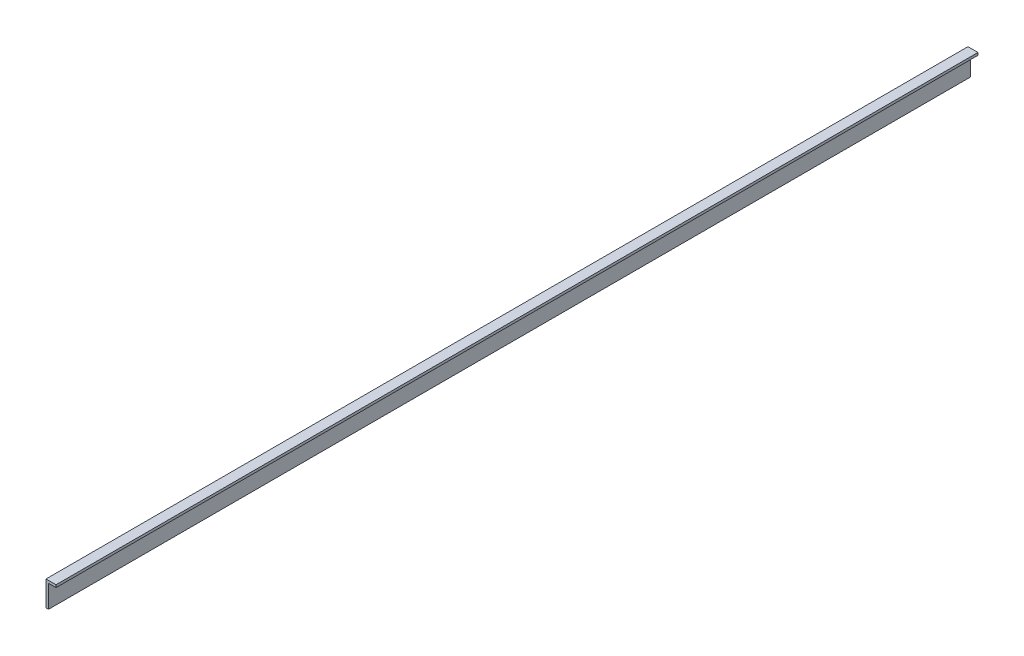
SolidWorks part; units mm, degrees
ref_plane "Front Plane" through (0, 0, 0) normal (0, 0, 1) x (1, 0, 0)
ref_plane "Top Plane" through (0, 0, 0) normal (0, 1, 0) x (1, 0, 0)
ref_plane "Right Plane" through (0, 0, 0) normal (1, 0, 0) x (0, 0, -1)
other "Configuration Table"
sketch "Sketch1" plane through (0, 0, 0) normal (0, 0, 1) x (1, 0, 0)
  line L0 (97.5, 404.5) -> (95.5, 404.5)
  line L1 (95.5, 404.5) -> (95.5, 424.5)
  line L2 (95.5, 424.5) -> (103.5, 424.5)
  line L3 (103.5, 424.5) -> (103.5, 422.5)
  line L4 (103.5, 422.5) -> (97.5, 422.5)
  line L5 (97.5, 422.5) -> (97.5, 404.5)
extrude "STORE_kaset_L_raf_1_sol_1" add sketch "Sketch1" against normal blind 735.5 from offset 20 separate body
